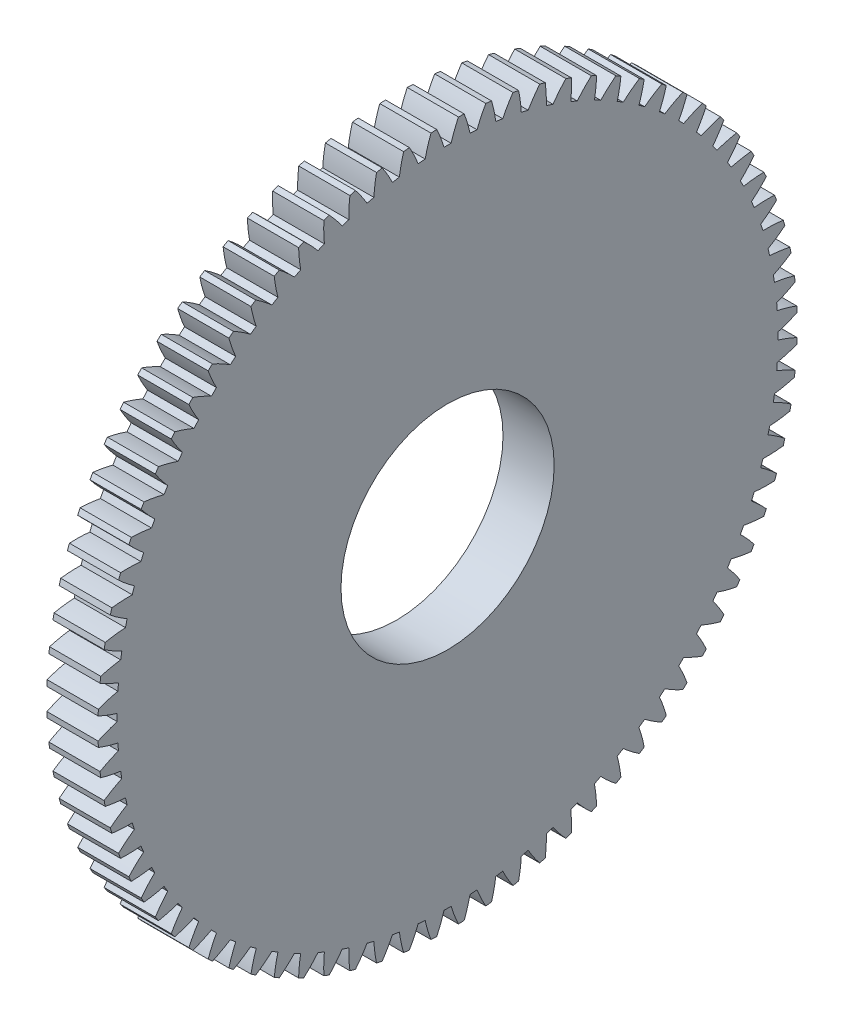
SolidWorks part; units mm, degrees
ref_plane "Plane1" through (0, 0, 0) normal (0, 0, 1) x (1, 0, 0)
ref_plane "Plane2" through (0, 0, 0) normal (0, 1, 0) x (1, 0, 0)
ref_plane "Plane3" through (0, 0, 0) normal (1, 0, 0) x (0, 0, -1)
other "Configuration Table"
sketch "HoldingSke" plane through (0, 0, 0) normal (0, 1, 0) x (1, 0, 0)
  line L0 (0, 0) -> (0.0868, -0.4924)
  line L1 (-15, 0) -> (100, 0) construction
  line L2 (0, 0) -> (-2.1039, 2.3779)
  line L3 (0, 0) -> (-11.863, 4.5341)
  line L4 (0, 0) -> (1.4996, 8.5048)
  line L5 (0, 0) -> (-46.8476, -17.4728)
  line L6 (0, 0) -> (-9.9476, -6.7116)
  line L7 (-2.1039, 2.3779) -> (8.6586, 51.2059)
  line L8 (-76.2, 54.61) -> (-71.9, 54.61)
  line L9 (-71.009, 38.7566) -> (-53.1078, 45.2721)
  line L10 (-76.2, 71.12) -> (104.1128, 71.12)
  line L11 (0, 0) -> (-12, 0)
  line L12 (-76.2, 101.6) -> (-76.133, 101.6)
  line L13 (24.9733, 27.94) -> (52.9518, 28.4284)
  line L14 (24.9733, 27.94) -> (24.9743, 27.94)
  line L15 (24.9733, 27.94) -> (100.4006, 29.5858)
  line L16 (-63.627, -2) -> (-12.827, -2)
  circle A0 centre (0, 0) radius 25
  circle A1 centre (0, 0) radius 37.5
  circle A2 centre (0, 0) radius 37.5
  circle A3 centre (0, 0) radius 25
  dimension "MHD" = 75
  dimension "Hub_dia" = 75
  dimension "Bore" = 50
  dimension "MBD" = 50
  dimension "Num_teeth" = 80
  dimension "Pitch" = 0.5
  dimension "Overall_len" = 50
  dimension "Show_teeth" = 80
  dimension "Thickness" = 12
  dimension "OAL" = 50.0001
  dimension "T_dim" = 4.3
  dimension "Ap" = 20
  dimension "H" = 19.05
  dimension "Pitch_radius" = 180.3128
  dimension "Width" = 12
  dimension "Backlash" = 0.067
  dimension "Addendum_fac" = 1
  dimension "Dedendum_fac" = 1.25
  dimension "Clearance_fac" = 0.25
  dimension "Dedendum_add" = 0.001
  dimension "Module" = 2
sketch "BasProSke" plane through (0, 0, 0) normal (0, 1, 0) x (1, 0, 0)
  line L0 (-10, 0) -> (60, 0) construction
  line L1 (0, 0) -> (0, 82)
  line L2 (0, 0) -> (12, 0)
  line L3 (12, 0) -> (12, 82)
  line L4 (12, 82) -> (0, 82)
  dimension "Thickness" = 12
  dimension "Diameter" = 164
revolve "Base-Revolve" add sketch "BasProSke" angle 360 about L0
sketch "TooCutSke" plane through (0, 0, 0) normal (1, 0, 0) x (0, 0, -1)
  line L1 (0, 0) -> (0, 107) construction
  line L2 (0, 0) -> (-1.6879, 79.9822) construction
  line L3 (0, 0) -> (-6.2805, 159.8503) construction
  line L4 (-1.6879, 79.9822) -> (-3.1403, 79.9251) construction
  arc A0 (0.8262, 77.4946) -> (-0.8262, 77.4946) centre (0, 0) ccw
  arc A1 (2.5557, 81.9856) -> (-2.5557, 81.9856) centre (0, 0) ccw
  circle A2 centre (0, 0) radius 80 construction
  circle A3 centre (0, 0) radius 75.1754 construction
  arc A4 (-0.8262, 77.4946) -> (-2.5557, 81.9856) centre (-31.4684, 68.2721) ccw
  arc A5 (2.5557, 81.9856) -> (0.8262, 77.4946) centre (31.4684, 68.2721) ccw
  dimension "Root_dia" = 154.998
  dimension "Overcut_dia" = 164.0508
  dimension "Pitch_dia" = 160
  dimension "Base_dia" = 150.3508
  dimension "Flank_rad" = 32
  dimension "Half_ang" = 2.25
  dimension "Half_CT" = 1.4534
extrude "ToothCut" cut sketch "TooCutSke" along normal through all
fillet "Breaks" [suppressed] radius 0.04
fillet "RootFillets" [suppressed] radius 0.501
pattern_circular "TeethCuts" count 80 every 4.5 about axis through (-10, 0, 0) along (1, 0, 0) of "ToothCut", "RootFillets", "Breaks"
sketch "HubNeaOneSke" plane through (0, 0, 0) normal (-1, 0, 0) x (0, 0, 1)
  circle A0 centre (0, 0) radius 37.5
  dimension "Diameter" = 75
extrude "HubNearOne" [suppressed] add sketch "HubNeaOneSke" along normal blind 38.0001
sketch "HubNeaBotSke" plane through (0, 0, 0) normal (-1, 0, 0) x (0, 0, 1)
  circle A0 centre (0, 0) radius 37.5
  dimension "Diameter" = 75
extrude "HubNearBoth" [suppressed] add sketch "HubNeaBotSke" along normal blind 19
ref_plane "FarPln" through (12, 0, 0) normal (1, 0, 0) x (0, 0, -1)
sketch "HubFarSke" plane through (12, 0, 0) normal (1, 0, 0) x (0, 0, -1)
  circle A0 centre (0, 0) radius 37.5
  dimension "Diameter" = 75
extrude "HubFar" [suppressed] add sketch "HubFarSke" along normal blind 19
sketch "BorSke" plane through (0, 0, 0) normal (1, 0, 0) x (0, 0, -1)
  circle A0 centre (0, 0) radius 25
  dimension "Diameter" = 50
extrude "Bore" cut sketch "BorSke" along normal mid plane 100.0001
sketch "KeySke" plane through (0, 0, 0) normal (1, 0, 0) x (0, 0, -1)
  line L0 (-8, 0) -> (-8, 29.3)
  line L1 (-8, 29.3) -> (8, 29.3)
  line L2 (8, 29.3) -> (8, 0)
  line L3 (0, 0) -> (0, 34) construction
  line L4 (-8, 0) -> (8, 0)
  dimension "Offset" = 29.3
  dimension "Width" = 16
extrude "Keyway" [suppressed] cut sketch "KeySke" along normal mid plane 100.0001
pattern_circular "Keyway2" [suppressed] count 2 every 90 about axis through (-10, 0, 0) along (1, 0, 0)
equation "' \"Module@HoldingSke\" = 6.35"
equation "' \"Num_teeth@HoldingSke\" = 12"
equation "' \"Ap@HoldingSke\" =  20"
equation "' \"Ap@HoldingSke\" = 20"
equation "' \"Width@HoldingSke\" = 0.5 * 25.4"
equation "' \"Hub_dia@HoldingSke\"= 1 * 25.4"
equation "' \"Hub_dia@HoldingSke\" = 1 * 25.4"
equation "' \"Overall_len@HoldingSke\" = 1.0 * 25.4"
equation "' \"Bore@HoldingSke\" = 0.75 * 25.4"
equation "' \"T_dim@HoldingSke\" = 0.1 * 25.4"
equation "' \"Width@KeySke\" = 0.25 * 25.4"
equation "' \"Show_teeth@HoldingSke\" = 13"
equation "' \"Backlash@HoldingSke\" = 0.009 * 25.4"
equation "' \"Addendum_fac@HoldingSke\" = 1.0"
equation "' \"Dedendum_fac@HoldingSke\" = 1.25"
equation "' \"Dedendum_add@HoldingSke\" = 0.00005 * 25.4"
equation "' \"Clearance_fac@HoldingSke\" = 0.25"
equation "\"Pitch@HoldingSke\" = 1 / \"Module@HoldingSke\""
equation "\"Overcut_dia@TooCutSke\" = (\"Num_teeth@HoldingSke\" + 2 * \"Addendum_fac@HoldingSke\") / \"Pitch@HoldingSke\" + 0.002 * 25.4"
equation "\"Pitch_dia@TooCutSke\" = \"Num_teeth@HoldingSke\" / \"Pitch@HoldingSke\""
equation "\"Base_dia@TooCutSke\" = \"Num_teeth@HoldingSke\" / \"Pitch@HoldingSke\" * cos((\"Ap@HoldingSke\"  * 3.14159265 / 180))"
equation "\"Root_dia@TooCutSke\" = (\"Num_teeth@HoldingSke\" + 2) / \"Pitch@HoldingSke\" - 2 * (\"Addendum_fac@HoldingSke\" + \"Dedendum_fac@HoldingSke\") / \"Pitch@HoldingSke\" - \"Dedendum_add@HoldingSke\" * 2"
equation "\"Half_ang@TooCutSke\" = 180 / \"Num_teeth@HoldingSke\""
equation "\"Half_CT@TooCutSke\" = \"Num_teeth@HoldingSke\" / \"Pitch@HoldingSke\" * sin((3.14159265 / 2 / \"Num_teeth@HoldingSke\")) / 2 - 7 * \"Backlash@HoldingSke\" / 4"
equation "\"Flank_rad@TooCutSke\" = \"Num_teeth@HoldingSke\" / \"Pitch@HoldingSke\" / 5"
equation "\"Radius@RootFillets\" = \"Clearance_fac@HoldingSke\" / \"Pitch@HoldingSke\" + \"Dedendum_add@HoldingSke\""
equation "\"Break_rad@Breaks\" = 0.02 / \"Pitch@HoldingSke\""
equation "\"Thickness@HoldingSke\" = \"Width@HoldingSke\""
equation "\"OAL@HoldingSke\" = \"Thickness@HoldingSke\""
equation "\"MHD@HoldingSke\" = (\"Num_teeth@HoldingSke\" + 2) / \"Pitch@HoldingSke\" - 2 * (\"Addendum_fac@HoldingSke\" + \"Dedendum_fac@HoldingSke\")  / \"Pitch@HoldingSke\" - \"Dedendum_add@HoldingSke\" * 2"
equation "\"MBD@HoldingSke\" = (\"Num_teeth@HoldingSke\" + 2) / \"Pitch@HoldingSke\" - 2 * (\"Addendum_fac@HoldingSke\" + \"Dedendum_fac@HoldingSke\")  / \"Pitch@HoldingSke\" - \"Dedendum_add@HoldingSke\" * 2 - 0.002 * 25.4"
equation "\"MHD@HoldingSke\" = ((sgn( \"MHD@HoldingSke\" - \"Hub_dia@HoldingSke\" )-1)*( \"MHD@HoldingSke\" - \"Hub_dia@HoldingSke\" ))/-2+ \"Hub_dia@HoldingSke\""
equation "\"MBD@HoldingSke\" = ((sgn( \"MBD@HoldingSke\" - \"Bore@HoldingSke\" )-1)*( \"MBD@HoldingSke\" - \"Bore@HoldingSke\" ))/-2+ \"Bore@HoldingSke\""
equation "\"OAL@HoldingSke\" = ((sgn( \"OAL@HoldingSke\" - \"Overall_len@HoldingSke\" )+1)*( \"OAL@HoldingSke\" - \"Overall_len@HoldingSke\" ))/2 + \"Overall_len@HoldingSke\" + 0.000002 * 25.4"
equation "\"Num_teeth@TeethCuts\" = int( \"Show_teeth@HoldingSke\" ) + 1"
equation "\"Num_teeth@TeethCuts\" = ((sgn( \"Num_teeth@TeethCuts\" - \"Num_teeth@HoldingSke\" )-1)*( \"Num_teeth@TeethCuts\" - \"Num_teeth@HoldingSke\" ))/-2+ \"Num_teeth@HoldingSke\""
equation "\"Num_teeth@TeethCuts\" = ((sgn( \"Num_teeth@TeethCuts\" - 2.0)+1)*( \"Num_teeth@TeethCuts\" - 2.0))/2 +2.0"
equation "\"Angle@TeethCuts\" = 360.0 / \"Num_teeth@HoldingSke\""
equation "\"Diameter@BasProSke\" = (\"Num_teeth@HoldingSke\" + 2 * \"Addendum_fac@HoldingSke\") / \"Pitch@HoldingSke\""
equation "\"Thickness@BasProSke\"  = \"Thickness@HoldingSke\""
equation "' \"Fillet_rad@BasProSke\" =  \"Thickness@HoldingSke\" * 0.05"
equation "' \"Fillet_rad@BasProSke\" = \"Thickness@HoldingSke\" * 0.05"
equation "\"MHD@HoldingSke\" = ((sgn( \"MHD@HoldingSke\" - \"Root_dia@TooCutSke\" )-1)*( \"MHD@HoldingSke\" - \"Root_dia@TooCutSke\" ))/-2+ \"Root_dia@TooCutSke\""
equation "\"Diameter@HubNeaOneSke\" = \"MHD@HoldingSke\""
equation "\"Length@HubNearOne\" = \"OAL@HoldingSke\" - \"Thickness@BasProSke\""
equation "\"Diameter@HubNeaBotSke\" = \"MHD@HoldingSke\""
equation "\"Length@HubNearBoth\" = ( \"OAL@HoldingSke\" - \"Thickness@BasProSke\" ) / 2.0"
equation "\"Thickness@FarPln\" = \"Thickness@BasProSke\""
equation "\"Diameter@HubFarSke\" = \"MHD@HoldingSke\""
equation "\"Length@HubFar\" = ( \"OAL@HoldingSke\" - \"Thickness@BasProSke\" ) / 2.0"
equation "\"Diameter@BorSke\" = \"MBD@HoldingSke\""
equation "\"D1@Bore\" = \"OAL@HoldingSke\" * 2.0"
equation "\"D1@Keyway\" = \"OAL@HoldingSke\" * 2.0"
equation "\"Offset@KeySke\" = \"T_dim@HoldingSke\" + \"MBD@HoldingSke\" / 2.0"
